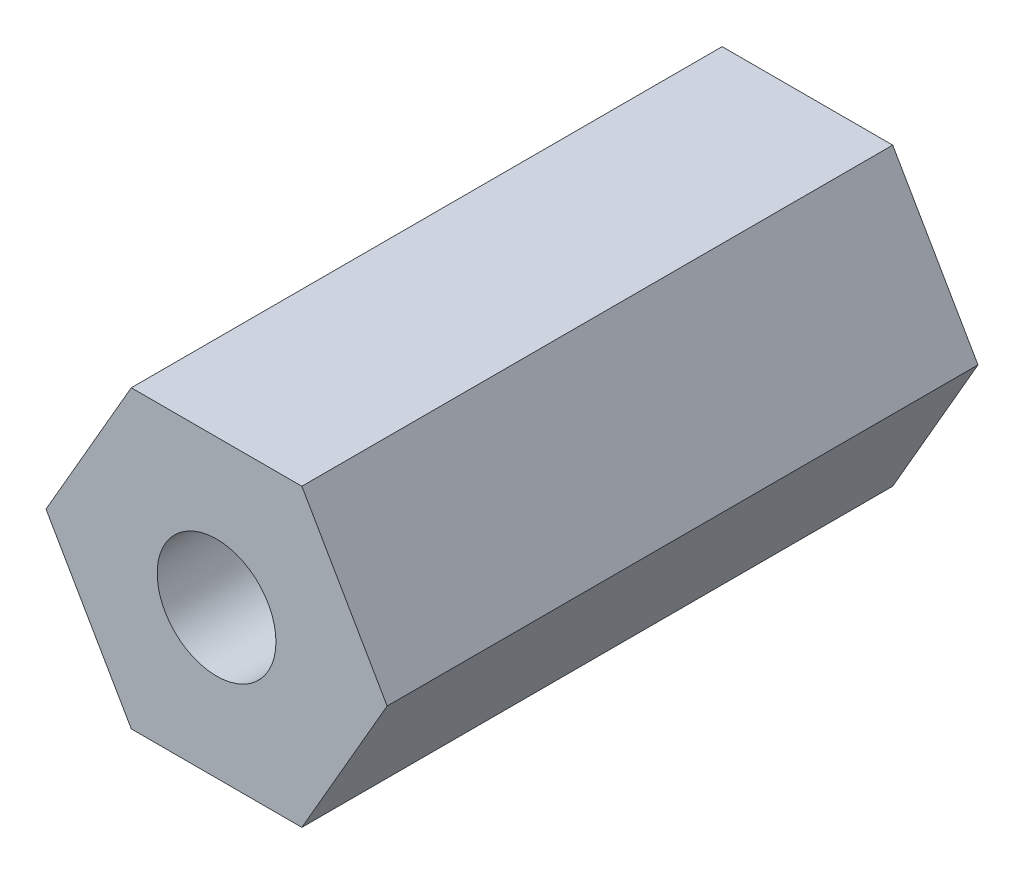
SolidWorks part; units mm, degrees
ref_plane "Front Plane" through (0, 0, 0) normal (0, 0, 1) x (1, 0, 0)
ref_plane "Top Plane" through (0, 0, 0) normal (0, 1, 0) x (1, 0, 0)
ref_plane "Right Plane" through (0, 0, 0) normal (1, 0, 0) x (0, 0, -1)
sketch "Sketch1" plane through (0, 0, 0) normal (0, 0, 1) x (1, 0, 0)
  line L1 (3.6662, -6.35) -> (7.3323, 0)
  line L2 (7.3323, 0) -> (3.6662, 6.35)
  line L3 (3.6662, 6.35) -> (-3.6662, 6.35)
  line L4 (-3.6662, 6.35) -> (-7.3323, 0)
  line L5 (-7.3323, 0) -> (-3.6662, -6.35)
  line L6 (-3.6662, -6.35) -> (3.6662, -6.35)
  circle A0 centre (0, 0) radius 6.35 construction
  circle A1 centre (0, 0) radius 2.5527
  dimension "D1" = 5.1054
  dimension "D2" = 12.7
extrude "Boss-Extrude1" add sketch "Sketch1" along normal blind 25.4
